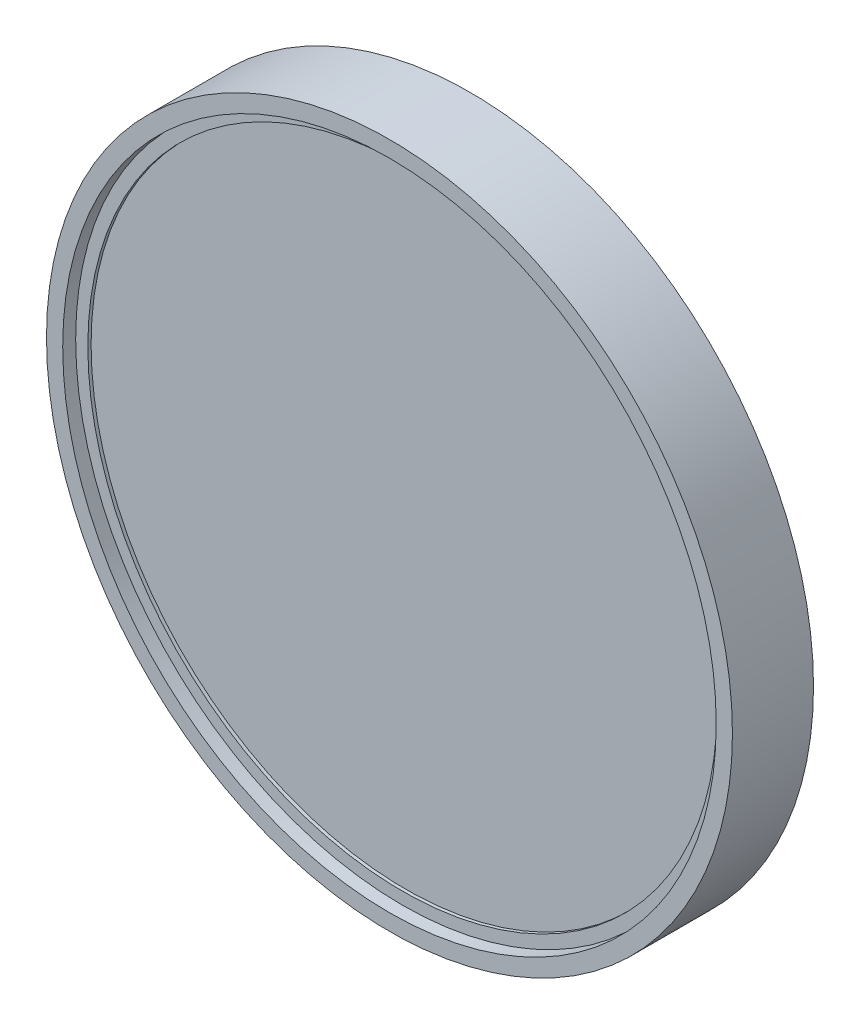
SolidWorks part; units mm, degrees
material "6061 Alloy"
ref_plane "Front Plane" through (0, 0, 0) normal (0, 0, 1) x (1, 0, 0)
ref_plane "Top Plane" through (0, 0, 0) normal (0, 1, 0) x (1, 0, 0)
ref_plane "Right Plane" through (0, 0, 0) normal (1, 0, 0) x (0, 0, -1)
sketch "Backer Main" plane through (0, 0, 0) normal (0, 0, 1) x (1, 0, 0)
  circle A0 centre (0, 0) radius 26.8605
  dimension "D1" = 53.721
extrude "Boss-Extrude1" add sketch "Backer Main" against normal blind 6.35
sketch "Substrate Back Clearance" plane through (0, 0, 0) normal (0, 0, 1) x (1, 0, 0)
  circle A0 centre (0, 0) radius 24.638
  dimension "D1" = 49.276
extrude "Cut-Extrude1" cut sketch "Substrate Back Clearance" against normal blind 1.27
sketch "Substrate CSink" plane through (0, 0, 0) normal (0, 0, 1) x (1, 0, 0)
  circle A0 centre (0, 0) radius 25.5905
  dimension "D1" = 51.181
extrude "Cut-Extrude2" cut sketch "Substrate CSink" against normal blind 1.016
sketch "Spring Hole" plane through (0, 0, -6.35) normal (0, 0, -1) x (-1, 0, 0)
  circle A0 centre (0, 0) radius 4.8895
  dimension "D1" = 9.779
extrude "Cut-Extrude3" cut sketch "Spring Hole" against normal blind 3.175
